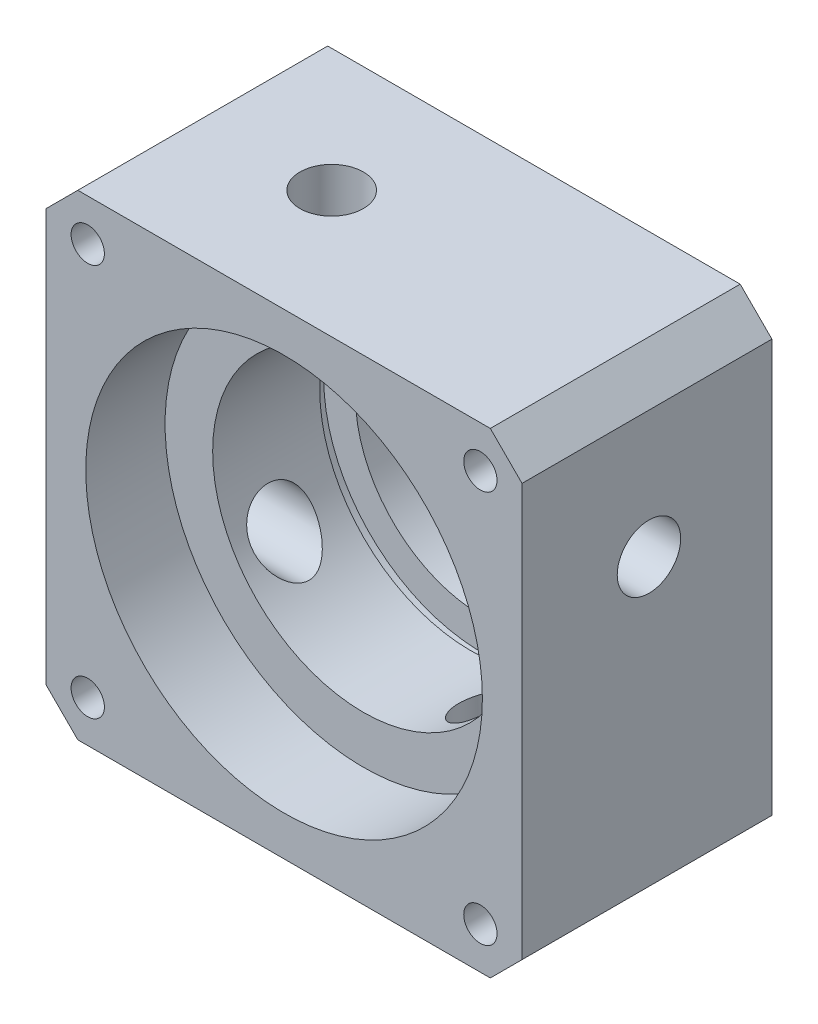
SolidWorks part; units mm, degrees
ref_plane "前视基准面" through (0, 0, 0) normal (0, 0, 1) x (1, 0, 0)
ref_plane "上视基准面" through (0, 0, 0) normal (0, 1, 0) x (1, 0, 0)
ref_plane "右视基准面" through (0, 0, 0) normal (1, 0, 0) x (0, 0, -1)
sketch "草图1" plane through (0, 0, 0) normal (0, 0, 1) x (1, 0, 0)
  line L0 (0, 0) -> (102.177, 0) construction
  line L1 (0, 0) -> (0, 85.271) construction
  line L2 (30, 26) -> (26, 30)
  line L3 (-26, -30) -> (26, -30)
  line L4 (-30, -26) -> (-30, 26)
  line L5 (-26, 30) -> (26, 30)
  line L6 (30, -26) -> (30, 26)
  line L7 (-30, -30) -> (30, 30) construction
  line L8 (-30, 30) -> (30, -30) construction
  line L9 (-30, 26) -> (-26, 30)
  line L10 (-26, -30) -> (-30, -26)
  line L11 (26, -30) -> (30, -26)
  circle A0 centre (0, 0) radius 19
  dimension "D3" = 38
  dimension "D1" = 60
  dimension "D2" = 60
extrude "凸台-拉伸1" add sketch "草图1" along normal blind 31.5
sketch "草图2" plane through (0, 0, 31.5) normal (0, 0, 1) x (1, 0, 0)
  circle A0 centre (0, 0) radius 25
  dimension "D1" = 50
extrude "切除-拉伸1" cut sketch "草图2" against normal blind 10
sketch "草图3" plane through (0, 0, 31.5) normal (0, 0, 1) x (1, 0, 0)
  line L0 (0, 0) -> (39.4275, 0) construction
  line L1 (0, 0) -> (28, 28) construction
  line L2 (30, 26) -> (26, 30) construction
  circle A0 centre (0, 0) radius 35
  dimension "D1" = 70
hole_wizard "M5 螺纹孔1" positions "草图5" profile "草图4" tap size "M5" standard "Gb"
sketch "草图5" plane through (0, 0, 31.5) normal (0, 0, 1) x (1, 0, 0)
  line L0 (0, 0) -> (28, 28) construction
  circle A0 centre (0, 0) radius 35 construction
  point P0 (24.7487, 24.7487)
sketch "草图4" plane through (24.7487, 24.7487, 31.5) normal (1, 0, 0) x (0, -1, 0)
  line L0 (0, 0) -> (0, 15.2618)
  line L1 (0, 15.2618) -> (2.1, 14)
  line L2 (2.1, 14) -> (2.1, 0)
  line L5 (2.1, 0) -> (0, 0)
  line L10 (0, 15.2618) -> (-2.1, 14) construction
  line L11 (0, -6.35) -> (0, 107.95) construction
  dimension "螺纹孔钻头直径" = 4.2
  dimension "螺纹孔钻头深度" = 14
  dimension "导头角度" = 118
cosmetic thread "孔螺蚊线1" parameters "D1"=10, "D2"=5
pattern_circular "阵列(圆周)1" count 4 over 360 about axis through (0, 0, 0) along (0, 0, 1) of "M5 螺纹孔1"
sketch "草图6" plane through (0, 0, 0) normal (0, 0, -1) x (-1, 0, 0)
  circle A0 centre (0, 0) radius 16
  circle A1 centre (0, 0) radius 19
  dimension "D1" = 32
extrude "凸台-拉伸2" add sketch "草图6" against normal blind 8
sketch "草图7" plane through (0, 0, 8) normal (0, 0, 1) x (1, 0, 0)
  circle A0 centre (0, 0) radius 20
  dimension "D1" = 40
extrude "切除-拉伸2" cut sketch "草图7" against normal blind 1.5
sketch "草图9" plane through (0, 30, 0) normal (0, 1, 0) x (1, 0, 0)
  line L0 (-30, -31.5) -> (-30, 0) construction
  line L1 (-35, -31.5) -> (35, -31.5) construction
  circle A0 centre (-10, -15.5) radius 4
  dimension "D1" = 8
  dimension "D2" = 20
  dimension "D3" = 16
extrude "切除-拉伸3" cut sketch "草图9" against normal blind 20
pattern_circular "阵列(圆周)2" count 4 over 360 about axis through (0, 0, 31.5) along (0, 0, -1) of "切除-拉伸3"
